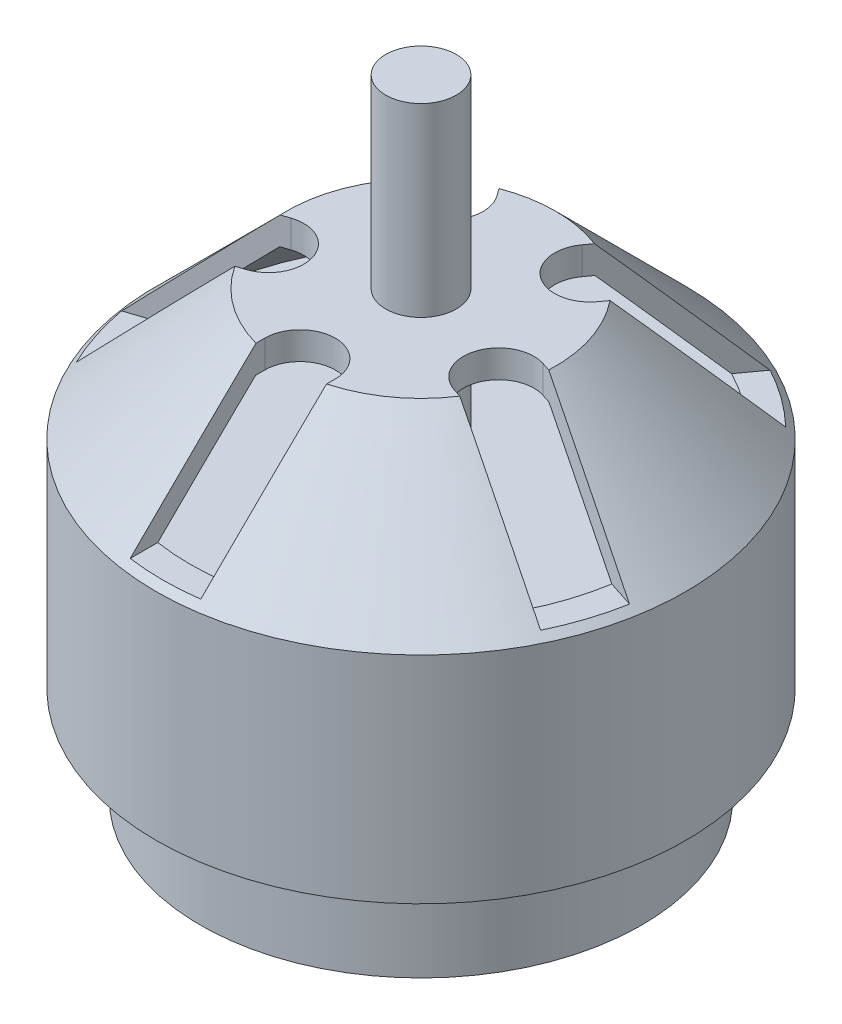
SolidWorks part; units mm, degrees
ref_plane "Front Plane" through (0, 0, 0) normal (0, 0, 1) x (1, 0, 0)
ref_plane "Top Plane" through (0, 0, 0) normal (0, 1, 0) x (1, 0, 0)
ref_plane "Right Plane" through (0, 0, 0) normal (1, 0, 0) x (0, 0, -1)
sketch "Sketch1" plane through (0, 0, 0) normal (0, 0, 1) x (1, 0, 0)
  line L0 (0, 0) -> (0, 71)
  line L1 (0, 71) -> (4, 71)
  line L2 (4, 71) -> (4, 50)
  line L3 (4, 50) -> (15.2417, 50)
  line L4 (15.2417, 50) -> (30, 35.2417)
  line L5 (30, 35.2417) -> (30, 10.8161)
  line L6 (30, 10.8161) -> (25, 10.8161)
  line L7 (25, 10.8161) -> (25, 0)
  line L8 (25, 0) -> (0, 0)
  line L9 (4, 46.8703) -> (15.2764, 46.8703)
  line L10 (15.2764, 46.8703) -> (26.9049, 35.2417)
  line L11 (26.9049, 35.2417) -> (4, 35.2417)
  line L12 (4, 35.2417) -> (4, 46.8703)
  dimension "D1" = 71
  dimension "D2" = 21
  dimension "D3" = 30
  dimension "D4" = 25
  dimension "D5" = 4
  dimension "D6" = 45
revolve "Revolve1" add sketch "Sketch1" angle 360 about L0
sketch "Sketch2" plane through (0, 50, 0) normal (0, 1, 0) x (1, 0, 0)
  line L0 (0, 0) -> (0, -9.7122) construction
  line L1 (4, -13.7122) -> (4, -33.0895)
  line L2 (4, -33.0895) -> (-4, -33.0895)
  line L3 (-4, -33.0895) -> (-4, -13.7122)
  line L4 (-30.2339, -14.0294) -> (-32.706, -6.421)
  line L5 (-11.805, -8.0415) -> (-30.2339, -14.0294)
  line L6 (-32.706, -6.421) -> (-14.2771, -0.4331)
  line L7 (-22.6856, 24.4188) -> (-16.2134, 29.1211)
  line L8 (-11.2959, 8.7423) -> (-22.6856, 24.4188)
  line L9 (-16.2134, 29.1211) -> (-4.8238, 13.4445)
  line L10 (16.2134, 29.1211) -> (22.6856, 24.4188)
  line L11 (4.8238, 13.4445) -> (16.2134, 29.1211)
  line L12 (22.6856, 24.4188) -> (11.2959, 8.7423)
  line L13 (32.706, -6.421) -> (30.2339, -14.0294)
  line L14 (14.2771, -0.4331) -> (32.706, -6.421)
  line L15 (30.2339, -14.0294) -> (11.805, -8.0415)
  arc A0 (4, -13.7122) -> (-4, -13.7122) centre (0, -13.7122) ccw
  arc A1 (-11.805, -8.0415) -> (-14.2771, -0.4331) centre (-13.0411, -4.2373) ccw
  arc A2 (-11.2959, 8.7423) -> (-4.8238, 13.4445) centre (-8.0598, 11.0934) ccw
  arc A3 (4.8238, 13.4445) -> (11.2959, 8.7423) centre (8.0598, 11.0934) ccw
  arc A4 (14.2771, -0.4331) -> (11.805, -8.0415) centre (13.0411, -4.2373) ccw
  point P31 (0, 0)
  dimension "D1" = 8
  dimension "D2" = 5
extrude "Cut-Extrude1" cut sketch "Sketch2" against normal blind 14
